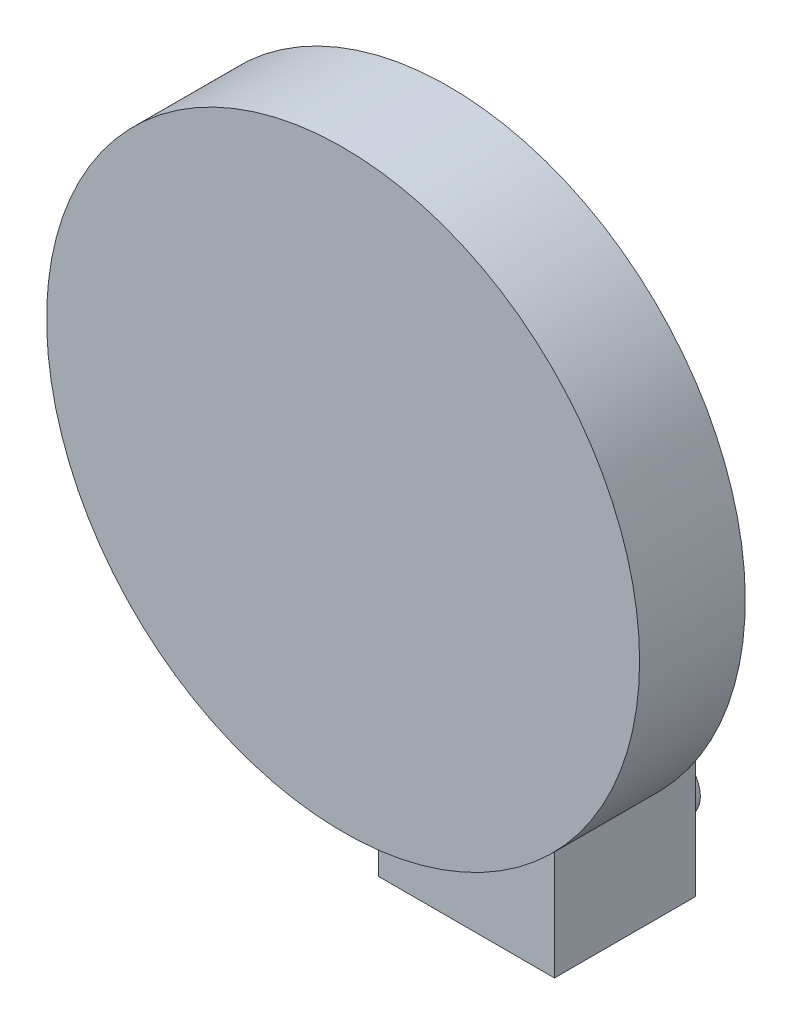
SolidWorks part; units mm, degrees
ref_plane "Front" through (0, 0, 0) normal (0, 0, 1) x (1, 0, 0)
ref_plane "Top" through (0, 0, 0) normal (0, 1, 0) x (1, 0, 0)
ref_plane "Right" through (0, 0, 0) normal (1, 0, 0) x (0, 0, -1)
sketch "Sketch1" plane through (0, 0, 0) normal (0, 0, 1) x (1, 0, 0)
  circle A0 centre (0, 0) radius 42.075
  dimension "D1" = 84.15
extrude "Boss-Extrude1" add sketch "Sketch1" along normal blind 15 contours A0
sketch "Sketch4" plane through (0, 0, 0) normal (0, 0, -1) x (-1, 0, 0)
  line L0 (0, 0) -> (10, 0)
  line L1 (10, 0) -> (-15, 0)
  line L2 (10, 0) -> (10, -60)
  line L3 (10, -60) -> (-15, -60)
  line L4 (-15, -60) -> (-15, 0)
  circle M2 centre (0, 0) radius 42.075
  dimension "D1" = 10
  dimension "D2" = 15
  dimension "D3" = 60
extrude "Boss-Extrude3" add sketch "Sketch4" along normal blind 20 contours L4 L2 L0 L1 M2 | L4 L3 L2 M2
sketch "Sketch8" plane through (0, 0, 15) normal (0, 0, 1) x (1, 0, 0)
  circle A0 centre (0, 0) radius 42.075
ref_plane "Plane1" through (0, 0, -20) normal (0, 0, -1) x (-1, 0, 0)
sketch "Sketch10" plane through (0, 0, -20) normal (0, 0, -1) x (-1, 0, 0)
  circle A0 centre (-3.6932, -55.3312) radius 4
extrude "Boss-Extrude8" add sketch "Sketch10" along normal blind 8
